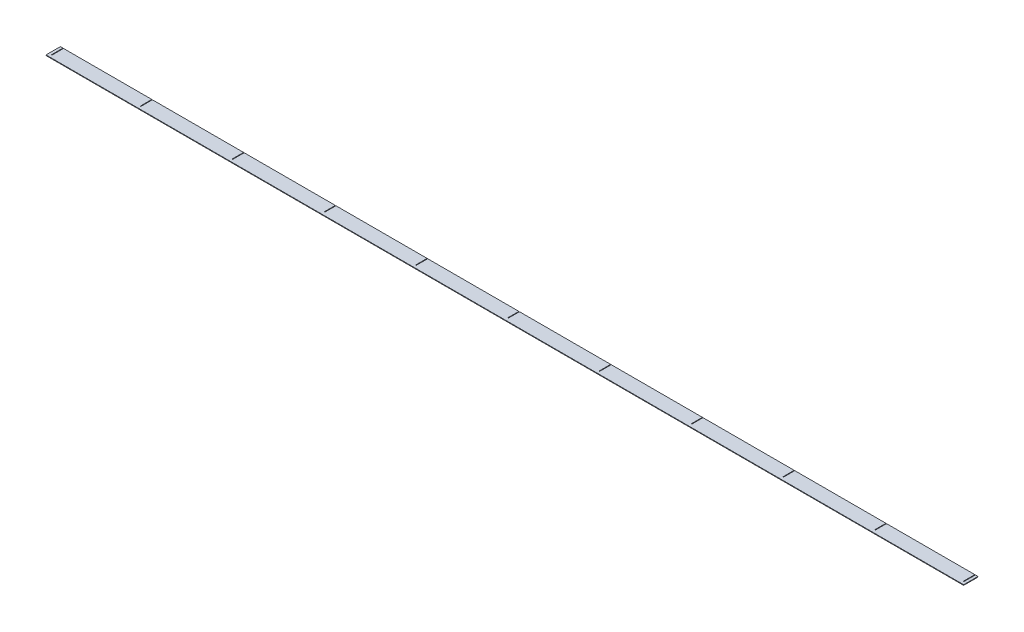
SolidWorks part; units mm, degrees
ref_plane "Front Plane" through (0, 0, 0) normal (0, 0, 1) x (1, 0, 0)
ref_plane "Top Plane" through (0, 0, 0) normal (0, 1, 0) x (1, 0, 0)
ref_plane "Right Plane" through (0, 0, 0) normal (1, 0, 0) x (0, 0, -1)
sketch "Sketch2" plane through (0, 0, 0) normal (0, 1, 0) x (1, 0, 0)
  line L0 (-800, -7.5) -> (800, -7.5) construction
  line L5 (-800, 12.5) -> (800, 12.5) construction
  line L6 (-800, 12.5) -> (-800, -12.5) construction
  line L7 (-800, -12.5) -> (800, -12.5) construction
  line L8 (800, 12.5) -> (800, -12.5) construction
  line L9 (-800, 12.5) -> (800, -12.5) construction
  line L10 (-800, -12.5) -> (800, 12.5) construction
  line L11 (-800, -12.5) -> (-800, 12.5)
  line L12 (-800, 12.5) -> (-795.5, 12.5)
  line L13 (-795.5, 12.5) -> (-795.5, -7.5)
  line L14 (-795.5, -7.5) -> (-794.5, -7.5)
  line L15 (-794.5, -7.5) -> (-794.5, 12.5)
  line L17 (-0.5, 12.5) -> (-0.5, -7.5)
  line L18 (-0.5, -7.5) -> (0.5, -7.5)
  line L19 (0.5, -7.5) -> (0.5, 12.5)
  line L21 (794.5, 12.5) -> (794.5, -7.5)
  line L22 (794.5, -7.5) -> (795.5, -7.5)
  line L23 (795.5, -7.5) -> (795.5, 12.5)
  line L24 (795.5, 12.5) -> (800, 12.5)
  line L25 (800, 12.5) -> (800, -12.5)
  line L26 (800, -12.5) -> (-800, -12.5)
  line L27 (-795, -7.5) -> (-795, 12.5) construction
  line L28 (795, -7.5) -> (795, 12.5) construction
  line L29 (0, 0) -> (0, -7.5) construction
  line L30 (160.5, -7.5) -> (160.5, 12.5)
  line L31 (160, 0) -> (160, -7.5) construction
  line L32 (159.5, 12.5) -> (159.5, -7.5)
  line L33 (159.5, -7.5) -> (160.5, -7.5)
  line L34 (320.5, -7.5) -> (320.5, 12.5)
  line L35 (320, 0) -> (320, -7.5) construction
  line L36 (319.5, 12.5) -> (319.5, -7.5)
  line L37 (319.5, -7.5) -> (320.5, -7.5)
  line L38 (480.5, -7.5) -> (480.5, 12.5)
  line L39 (480, 0) -> (480, -7.5) construction
  line L40 (479.5, 12.5) -> (479.5, -7.5)
  line L41 (479.5, -7.5) -> (480.5, -7.5)
  line L42 (640.5, -7.5) -> (640.5, 12.5)
  line L43 (640, 0) -> (640, -7.5) construction
  line L44 (639.5, 12.5) -> (639.5, -7.5)
  line L45 (639.5, -7.5) -> (640.5, -7.5)
  line L46 (-159.5, -7.5) -> (-159.5, 12.5)
  line L47 (-160.5, -7.5) -> (-159.5, -7.5)
  line L48 (-160.5, 12.5) -> (-160.5, -7.5)
  line L49 (-160, 0) -> (-160, -7.5) construction
  line L50 (-319.5, -7.5) -> (-319.5, 12.5)
  line L51 (-320.5, -7.5) -> (-319.5, -7.5)
  line L52 (-320.5, 12.5) -> (-320.5, -7.5)
  line L53 (-320, 0) -> (-320, -7.5) construction
  line L54 (-479.5, -7.5) -> (-479.5, 12.5)
  line L55 (-480.5, -7.5) -> (-479.5, -7.5)
  line L56 (-480.5, 12.5) -> (-480.5, -7.5)
  line L57 (-480, 0) -> (-480, -7.5) construction
  line L58 (-639.5, -7.5) -> (-639.5, 12.5)
  line L59 (-640.5, -7.5) -> (-639.5, -7.5)
  line L60 (-640.5, 12.5) -> (-640.5, -7.5)
  line L61 (-640, 0) -> (-640, -7.5) construction
  line L62 (-794.5, 12.5) -> (-640.5, 12.5)
  line L63 (-639.5, 12.5) -> (-480.5, 12.5)
  line L64 (-479.5, 12.5) -> (-320.5, 12.5)
  line L65 (-319.5, 12.5) -> (-160.5, 12.5)
  line L66 (-159.5, 12.5) -> (-0.5, 12.5)
  line L67 (0.5, 12.5) -> (159.5, 12.5)
  line L68 (160.5, 12.5) -> (319.5, 12.5)
  line L69 (320.5, 12.5) -> (479.5, 12.5)
  line L70 (480.5, 12.5) -> (639.5, 12.5)
  line L71 (640.5, 12.5) -> (794.5, 12.5)
  point P0 (0, 0)
  point P27 (-160, -3.75)
  dimension "D1" = 5
  dimension "D2" = 25
  dimension "D3" = 5
  dimension "D4" = 1
  dimension "D5" = 1
  dimension "D6" = 5
  dimension "D7" = 1600
  dimension "D8" = 1
  dimension "D10" = 160
  dimension "D12" = 160
  dimension "D9" = 5
  dimension "D11" = 5
extrude "Boss-Extrude1" add sketch "Sketch2" along normal blind 1
